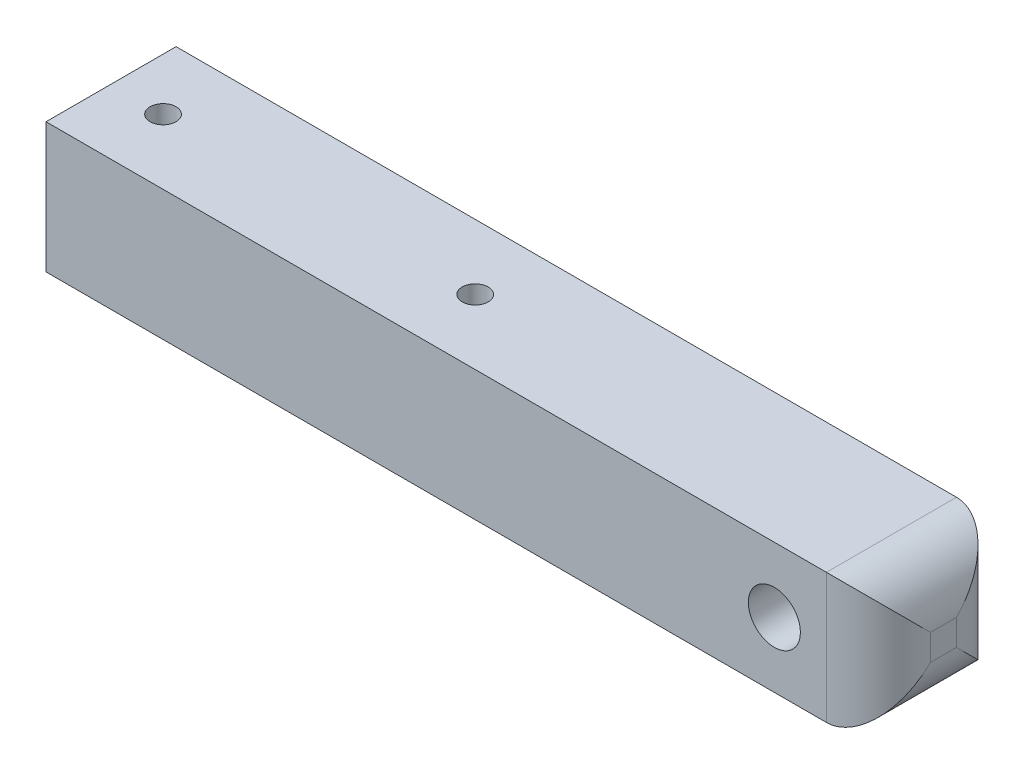
SolidWorks part; units mm, degrees
ref_plane "Front Plane" through (0, 0, 0) normal (0, 0, 1) x (1, 0, 0)
ref_plane "Top Plane" through (0, 0, 0) normal (0, 1, 0) x (1, 0, 0)
ref_plane "Right Plane" through (0, 0, 0) normal (1, 0, 0) x (0, 0, -1)
sketch "Sketch1" plane through (0, 0, 0) normal (0, 0, 1) x (1, 0, 0)
  line L0 (0, 0) -> (101.6, 0)
  line L1 (101.6, 0) -> (101.6, 31.75)
  line L2 (101.6, 31.75) -> (-101.6, 31.75)
  line L3 (-101.6, 31.75) -> (-101.6, 0)
  line L4 (-101.6, 0) -> (0, 0)
  dimension "D1" = 31.75
  dimension "D2" = 203.2
extrude "Boss-Extrude1" add sketch "Sketch1" along normal mid plane 31.75
sketch "Sketch2" plane through (-101.6, 0, 0) normal (-1, 0, 0) x (0, 0, 1)
  line L0 (0, 4.9711) -> (-8.9803, 13.9513)
  line L1 (-8.9803, 13.9513) -> (-9.8783, 13.0533)
  line L2 (-9.8783, 13.0533) -> (0, 3.175)
  line L3 (0, 3.175) -> (9.8783, 13.0533)
  line L4 (9.8783, 13.0533) -> (8.9803, 13.9513)
  line L5 (8.9803, 13.9513) -> (0, 4.9711)
  line L6 (-11.3146, 0) -> (21.0706, 0) construction
  line L7 (-15.875, 31.75) -> (-15.875, 0) construction
  line L8 (-9.8783, 13.0533) -> (-15.875, 13.0533) construction
  line L9 (9.8783, 13.0533) -> (15.875, 13.0533) construction
  line L10 (15.875, 31.75) -> (15.875, 0) construction
  dimension "D1" = 1.27
  dimension "D2" = 3.175
  dimension "D3" = 12.7
extrude "Cut-Extrude1" cut sketch "Sketch2" against normal blind 152.4
hole_wizard "1/2 (0.5) Diameter Hole1" positions "Sketch3" profile "Sketch4" hole size "1/2" standard "ANSI Inch" end condition through all
sketch "Sketch3" plane through (0, 0, 15.875) normal (0, 0, 1) x (1, 0, 0)
  line L0 (-101.6, 31.75) -> (-101.6, 0) construction
  line L1 (-101.6, 15.875) -> (162.3719, 15.875) construction
  point P0 (76.2, 15.875)
  dimension "D1" = 177.8
sketch "Sketch4" plane through (76.2, 15.875, 15.875) normal (1, 0, 0) x (0, -1, 0)
  line L0 (0, 0) -> (0, 31.75)
  line L1 (0, 31.75) -> (6.35, 31.75)
  line L2 (6.35, 31.75) -> (6.35, 0)
  line L5 (6.35, 0) -> (0, 0)
  line L11 (0, -6.35) -> (0, 107.95) construction
  dimension "Thru Hole Dia." = 12.7
  dimension "Thru Hole Depth" = 31.75
hole_wizard "1/4 (0.25) Diameter Hole1" positions "Sketch5" profile "Sketch6" hole size "1/4" standard "ANSI Inch" end condition through all
sketch "Sketch5" plane through (0, 31.75, 0) normal (0, 1, 0) x (1, 0, 0)
  line L0 (-101.6, -15.875) -> (-101.6, 15.875) construction
  point P0 (-88.9, 0)
  point P2 (-12.7, 0)
  dimension "D1" = 12.7
  dimension "D2" = 76.2
sketch "Sketch6" plane through (-88.9, 31.75, 0) normal (1, 0, 0) x (0, 0, 1)
  line L0 (0, 0) -> (0, 31.75)
  line L1 (0, 31.75) -> (3.175, 31.75)
  line L2 (3.175, 31.75) -> (3.175, 0)
  line L5 (3.175, 0) -> (0, 0)
  line L11 (0, -6.35) -> (0, 107.95) construction
  dimension "Thru Hole Dia." = 6.35
  dimension "Thru Hole Depth" = 31.75
fillet "Fillet1" radius 12.7 4 edges at (101.6, 0, 0) (101.6, 15.875, -15.875) (101.6, 31.75, 0) (101.6, 15.875, 15.875)
